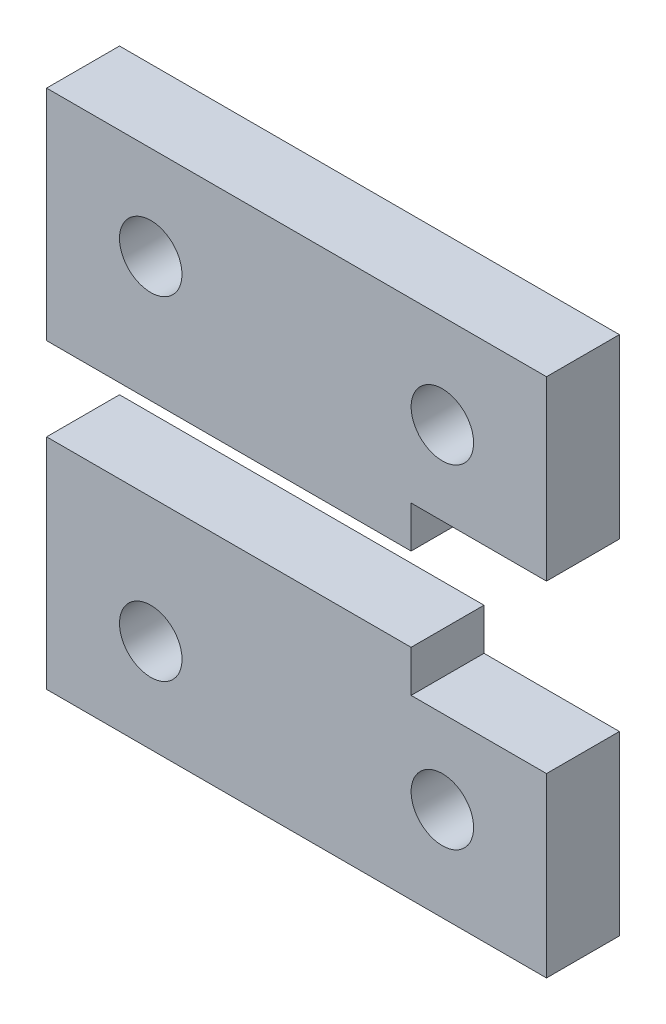
SolidWorks part; units mm, degrees
ref_plane "Alzado" through (0, 0, 0) normal (0, 0, 1) x (1, 0, 0)
ref_plane "Planta" through (0, 0, 0) normal (0, 1, 0) x (1, 0, 0)
ref_plane "Vista lateral" through (0, 0, 0) normal (1, 0, 0) x (0, 0, -1)
sketch "Croquis1" plane through (0, 0, 0) normal (0, 0, 1) x (1, 0, 0)
  line L0 (17.5, 8.5) -> (17.5, 10.5)
  line L1 (0, 0) -> (24, 0)
  line L2 (-8.4794, 12.5) -> (35.2431, 12.5) construction
  line L3 (17.5, 8.5) -> (24, 8.5)
  line L4 (24, 0) -> (24, 8.5)
  line L5 (17.5, 10.5) -> (0, 10.5)
  line L6 (0, 10.5) -> (0, 0)
  line L7 (0, 14.5) -> (0, 25)
  line L8 (17.5, 14.5) -> (0, 14.5)
  line L9 (24, 25) -> (24, 16.5)
  line L10 (17.5, 16.5) -> (24, 16.5)
  line L11 (0, 25) -> (24, 25)
  line L12 (17.5, 16.5) -> (17.5, 14.5)
  circle A0 centre (5, 4.5) radius 1.5
  circle A1 centre (19, 4.5) radius 1.5
  circle A2 centre (19, 20.5) radius 1.5
  circle A3 centre (5, 20.5) radius 1.5
  dimension "D3" = 3
  dimension "D4" = 3
  dimension "D1" = 24
  dimension "D2" = 4
  dimension "D5" = 14
  dimension "D6" = 5
  dimension "D7" = 4.5
  dimension "D8" = 2
  dimension "D9" = 6.5
  dimension "D10" = 2
extrude "Saliente-Extruir1" add sketch "Croquis1" along normal blind 3.5
